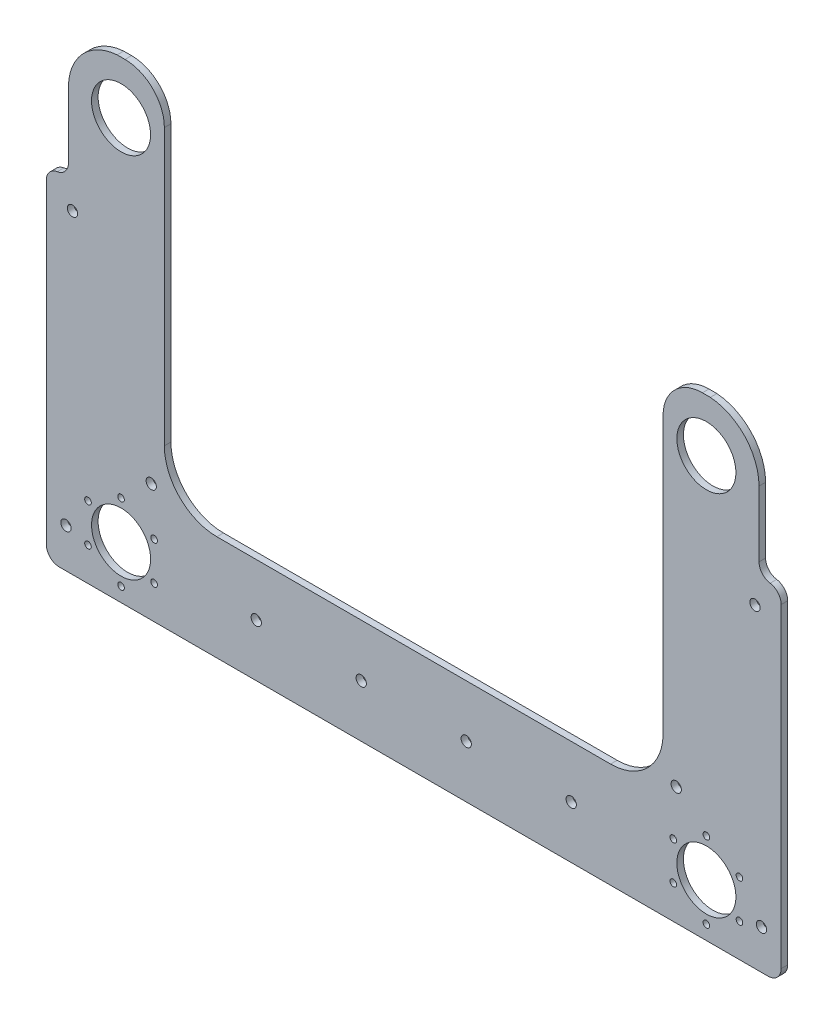
SolidWorks part; units mm, degrees
material "6061 Alloy"
ref_plane "Front Plane" through (0, 0, 0) normal (0, 0, 1) x (1, 0, 0)
ref_plane "Top Plane" through (0, 0, 0) normal (0, 1, 0) x (1, 0, 0)
ref_plane "Right Plane" through (0, 0, 0) normal (1, 0, 0) x (0, 0, -1)
sketch "Sketch1" plane through (0, 0, 0) normal (0, 0, 1) x (1, 0, 0)
  line L5 (120.65, -152.4) -> (120.65, -6.35)
  line L6 (127, 0) -> (171.45, 0) construction
  line L7 (177.8, -6.35) -> (177.8, -222.25)
  line L10 (0, -206.2199) -> (0, -63.6275) construction
  line L11 (-54.9244, 0) -> (300.6756, 0) construction
  line L13 (12.7, -177.8) -> (95.25, -177.8)
  line L14 (12.7, -228.6) -> (171.45, -228.6)
  line L15 (141.605, -25.4) -> (141.605, -84.2822) construction
  line L16 (141.605, -25.4) -> (141.605, -127) construction
  line L17 (-141.605, -25.4) -> (-141.605, -203.2) construction
  line L18 (-141.605, -25.4) -> (-141.605, -127) construction
  line L19 (-141.605, -19.0512) -> (-141.605, -77.9333) construction
  line L20 (141.605, -25.4) -> (141.605, -203.2) construction
  line L22 (-120.65, -152.4) -> (-120.65, -6.35)
  line L23 (-12.7, -177.8) -> (-95.25, -177.8)
  line L24 (-12.7, -228.6) -> (-171.45, -228.6)
  line L25 (-177.8, -6.35) -> (-177.8, -222.25)
  line L26 (-12.7, -177.8) -> (12.7, -177.8)
  line L27 (-12.7, -228.6) -> (12.7, -228.6)
  line L28 (-177.8, -6.35) -> (-177.8, 6.35)
  line L29 (-165.1, 19.05) -> (-133.35, 19.05)
  line L30 (-120.65, 6.35) -> (-120.65, -6.35)
  line L31 (120.65, 6.35) -> (120.65, -6.35)
  line L32 (177.8, -6.35) -> (177.8, 6.35)
  line L33 (165.1, 19.05) -> (133.35, 19.05)
  arc A0 (95.25, -177.8) -> (120.65, -152.4) centre (95.25, -152.4) ccw
  arc A4 (120.65, -6.35) -> (127, 0) centre (127, -6.35) cw construction
  circle A8 centre (141.605, -25.4) radius 14.2875
  circle A9 centre (141.605, -25.4) radius 38.1 construction
  arc A10 (177.8, -6.35) -> (171.45, 0) centre (171.45, -6.35) ccw construction
  arc A11 (171.45, -228.6) -> (177.8, -222.25) centre (171.45, -222.25) ccw
  arc A14 (141.605, -82.55) -> (120.9214, -78.6758) centre (141.605, -25.4) ccw construction
  arc A15 (-141.605, -82.55) -> (-120.9214, -78.6758) centre (-141.605, -25.4) cw construction
  circle A16 centre (-141.605, -25.4) radius 38.1 construction
  circle A17 centre (-141.605, -25.4) radius 14.2875
  arc A19 (-95.25, -177.8) -> (-120.65, -152.4) centre (-95.25, -152.4) cw
  circle A20 centre (141.605, -127) radius 38.1 construction
  circle A21 centre (-141.605, -127) radius 38.1 construction
  arc A23 (-171.45, -228.6) -> (-177.8, -222.25) centre (-171.45, -222.25) cw
  circle A24 centre (-141.605, -203.2) radius 14.2875
  circle A25 centre (-141.605, -184.7248) radius 1.6002
  circle A26 centre (-125.604, -193.963) radius 1.6002
  circle A27 centre (-125.604, -212.4393) radius 1.6002
  circle A28 centre (-141.605, -221.6775) radius 1.6002
  circle A29 centre (-157.606, -212.4393) radius 1.6002
  circle A30 centre (-157.606, -193.963) radius 1.6002
  circle A31 centre (157.606, -212.4393) radius 1.6002
  circle A32 centre (157.606, -193.963) radius 1.6002
  circle A33 centre (141.605, -184.7248) radius 1.6002
  circle A34 centre (125.604, -193.963) radius 1.6002
  circle A35 centre (125.604, -212.4393) radius 1.6002
  circle A36 centre (141.605, -221.6775) radius 1.6002
  circle A37 centre (141.605, -203.2) radius 14.2875
  circle A39 centre (-76.2, -203.2) radius 2.4892
  circle A40 centre (76.2, -203.2) radius 2.4892
  circle A42 centre (-25.4, -203.2) radius 2.4892
  circle A43 centre (-127, -171.45) radius 2.4892
  arc A44 (-133.35, 19.05) -> (-120.65, 6.35) centre (-133.35, 6.35) cw
  arc A45 (-177.8, 6.35) -> (-165.1, 19.05) centre (-165.1, 6.35) cw
  arc A46 (133.35, 19.05) -> (120.65, 6.35) centre (133.35, 6.35) ccw
  arc A47 (177.8, 6.35) -> (165.1, 19.05) centre (165.1, 6.35) ccw
  circle A50 centre (-149.225, 6.35) radius 2.4892
  circle A51 centre (127, -171.45) radius 2.4892
  circle A53 centre (149.225, 6.35) radius 2.4892
  circle A54 centre (-168.275, -209.55) radius 2.4892
  circle A56 centre (168.275, -209.55) radius 2.4892
  circle A58 centre (-165.1, -76.2) radius 2.4892
  circle A59 centre (165.1, -76.2) radius 2.4892
  circle A60 centre (25.4, -203.2) radius 2.4892
  point P2 (177.8, -44.45)
  point P18 (177.8, 0)
  point P23 (177.8, -228.6)
  point P24 (177.8, -228.6)
  point P31 (177.8, 0)
  point P48 (-177.8, 0)
  point P49 (-177.8, -228.6)
  point P51 (-177.8, -44.45)
  point P78 (-141.605, -203.2012)
  dimension "D6" = 25.4
  dimension "D7" = 6.35
  dimension "D8" = 6.35
  dimension "D9" = 177.8
  dimension "D10" = 28.575
  dimension "D12" = 76.2
  dimension "D13" = 57.15
  dimension "D15" = 28.575
  dimension "D18" = 76.2
  dimension "D21" = 3.2004
  dimension "D29" = 9.525
  dimension "D32" = 4.9784
  dimension "D35" = 4.9784
  dimension "D37" = 4.9784
  dimension "D40" = 12.7
  dimension "D43" = 4.9784
  dimension "D45" = 12.7
  dimension "D30" = 4.9784
  dimension "D41" = 4.9784
  dimension "D2" = 120.65
  dimension "D3" = 177.8
  dimension "D4" = 228.6
  dimension "D5" = 177.8
  dimension "D11" = 20.955
  dimension "`" = 25.4
  dimension "D14" = 57.15
  dimension "D16" = 184.15
  dimension "D17" = 101.6
  dimension "D19" = 25.4
  dimension "D20" = 101.6
  dimension "D22" = 0
  dimension "D23" = 18.4752
  dimension "D25" = 6.9225
  dimension "D26" = 19.05
  dimension "D27" = 25.4
  dimension "D28" = 25.4
  dimension "D31" = 95.25
  dimension "D33" = 12.7
  dimension "D34" = 25.4
  dimension "D38" = 57.15
  dimension "D39" = 19.05
  dimension "D42" = 6.35
  dimension "D44" = 28.575
  dimension "D46" = 25.4
  dimension "D24" = 6
extrude "Boss-Extrude3" add sketch "Sketch1" along normal blind 3.175
sketch "Sketch2" plane through (0, 0, 3.175) normal (0, 0, 1) x (1, 0, 0)
  line L0 (-133.35, 19.05) -> (-165.1, 19.05) construction
  line L1 (-177.8, 19.05) -> (177.8, 19.05)
  line L2 (-177.8, 19.05) -> (-177.8, 0)
  line L3 (-177.8, 0) -> (177.8, 0)
  line L4 (177.8, 19.05) -> (177.8, 0)
  line L5 (-177.8, 6.35) -> (-177.8, -222.25) construction
  line L6 (177.8, -222.25) -> (177.8, 6.35) construction
  dimension "D1" = 19.05
extrude "Cut-Extrude1" cut sketch "Sketch2" against normal through all
fillet "Fillet1" radius 19.05 4 edges at (177.8, 0, 1.5875) (120.65, 0, 1.5875) (-120.65, 0, 1.5875) (-177.8, 0, 1.5875)
sketch "Sketch3" plane through (0, 0, 3.175) normal (0, 0, 1) x (1, 0, 0)
  line L0 (-167.0763, -25.4) -> (-167.0763, -57.15)
  line L1 (-173.4263, -63.5) -> (-177.8, -63.5)
  line L2 (-177.8, -19.05) -> (-177.8, -222.25) construction
  line L3 (-158.75, 0) -> (-139.7, 0) construction
  line L4 (-177.8, -63.5) -> (-177.8, 0)
  line L5 (-177.8, 0) -> (-139.7, 0)
  circle A0 centre (-141.605, -25.4) radius 25.4713 construction
  arc A1 (-120.65, -19.05) -> (-139.7, 0) centre (-139.7, -19.05) ccw construction
  arc A2 (-120.65, -19.05) -> (-139.7, 0) centre (-139.7, -19.05) ccw construction
  arc A3 (-139.7, 0) -> (-167.0763, -25.4) centre (-141.605, -25.4) ccw
  arc A4 (-167.0763, -57.15) -> (-173.4263, -63.5) centre (-173.4263, -57.15) cw
  arc M19 (-158.75, 0) -> (-177.8, -19.05) centre (-158.75, -19.05) ccw
  line M20 (-177.8, -19.05) -> (-177.8, -222.25)
  dimension "D1" = 63.5
  dimension "D2" = 6.35
extrude "Cut-Extrude2" cut sketch "Sketch3" against normal through all contours L5 L4 M19 | A4 L0 A3 L5 L1 M19 M20
ref_plane "Plane1" through (0, 0, 0) normal (1, 0, 0) x (0, 0, -1)
mirror "Mirror1" about plane through (0, 0, 0) normal (1, 0, 0) of "Cut-Extrude2"
fillet "Fillet2" radius 6.35 2 edges at (177.8, -63.5, 1.5875) (-177.8, -63.5, 1.5875)
